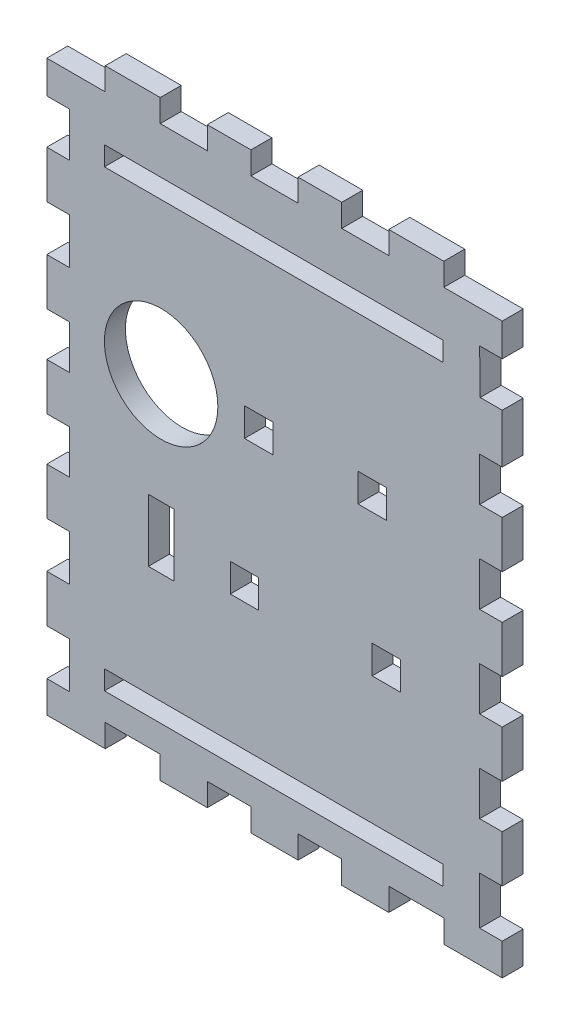
SolidWorks part; units mm, degrees
ref_plane "Front Plane" through (0, 0, 0) normal (0, 0, 1) x (1, 0, 0)
ref_plane "Top Plane" through (0, 0, 0) normal (0, 1, 0) x (1, 0, 0)
ref_plane "Right Plane" through (0, 0, 0) normal (1, 0, 0) x (0, 0, -1)
sketch "Model" plane through (0, 0, 0) normal (0, 0, 1) x (1, 0, 0)
  line L0 (11.6457, 131.1853) -> (7.6593, 131.1853)
  line L1 (7.6593, 131.1853) -> (7.6593, 139.4756)
  line L2 (7.6593, 139.4756) -> (11.6457, 139.4756)
  line L3 (11.6457, 139.4756) -> (11.6457, 147.1661)
  line L4 (11.6457, 147.1661) -> (7.6593, 147.1661)
  line L5 (7.6593, 147.1661) -> (7.6593, 155.4564)
  line L6 (7.6593, 155.4564) -> (11.6457, 155.4564)
  line L7 (11.6457, 155.4564) -> (11.6457, 163.1823)
  line L8 (11.6457, 163.1823) -> (7.6593, 163.1823)
  line L9 (7.6593, 163.1823) -> (7.6593, 171.4725)
  line L10 (7.6593, 171.4725) -> (11.6457, 171.4725)
  line L11 (87.9515, 101.1639) -> (77.6504, 101.1639)
  line L12 (77.6504, 101.1639) -> (77.6504, 105.1856)
  line L13 (77.6504, 105.1856) -> (67.949, 105.1856)
  line L14 (67.949, 105.1856) -> (67.949, 101.1639)
  line L15 (67.949, 101.1639) -> (59.6588, 101.1639)
  line L16 (59.6588, 101.1639) -> (59.6588, 105.1856)
  line L17 (59.6588, 105.1856) -> (51.9682, 105.1856)
  line L18 (51.9682, 105.1856) -> (51.9682, 101.1639)
  line L19 (51.9682, 101.1639) -> (43.6427, 101.1639)
  line L20 (43.6427, 101.1639) -> (43.6427, 105.1856)
  line L21 (43.6427, 105.1856) -> (35.9521, 105.1856)
  line L22 (35.9521, 105.1856) -> (35.9521, 101.1639)
  line L23 (35.9521, 101.1639) -> (27.6618, 101.1639)
  line L24 (27.6618, 101.1639) -> (27.6618, 105.1856)
  line L25 (27.6618, 105.1856) -> (17.9604, 105.1856)
  line L26 (17.9604, 105.1856) -> (17.9604, 101.1639)
  line L27 (17.9604, 101.1639) -> (7.6593, 101.1639)
  line L28 (87.9515, 179.1631) -> (83.9652, 179.1631)
  line L29 (83.9652, 179.1631) -> (83.9652, 171.4725)
  line L30 (83.9652, 171.4725) -> (87.9515, 171.4725)
  line L31 (87.9515, 171.4725) -> (87.9515, 163.1823)
  line L32 (87.9515, 163.1823) -> (83.9652, 163.1823)
  line L33 (83.9652, 163.1823) -> (83.9652, 155.4564)
  line L34 (83.9652, 155.4564) -> (87.9515, 155.4564)
  line L35 (87.9515, 155.4564) -> (87.9515, 147.1661)
  line L36 (87.9515, 147.1661) -> (83.9652, 147.1661)
  line L37 (83.9652, 147.1661) -> (83.9652, 139.4756)
  line L38 (83.9652, 139.4756) -> (87.9515, 139.4756)
  line L39 (87.9515, 139.4756) -> (87.9515, 131.1853)
  line L40 (87.9515, 131.1853) -> (83.9652, 131.1853)
  line L41 (87.9515, 201.4586) -> (77.6504, 201.4586)
  line L42 (77.6504, 201.4586) -> (77.6504, 205.445)
  line L43 (77.6504, 205.445) -> (67.949, 205.445)
  line L44 (67.949, 205.445) -> (67.949, 201.4586)
  line L45 (67.949, 201.4586) -> (59.6588, 201.4586)
  line L46 (59.6588, 201.4586) -> (59.6588, 205.445)
  line L47 (59.6588, 205.445) -> (51.9682, 205.445)
  line L48 (51.9682, 205.445) -> (51.9682, 201.4586)
  line L49 (51.9682, 201.4586) -> (43.6427, 201.4586)
  line L50 (43.6427, 201.4586) -> (43.6427, 205.445)
  line L51 (43.6427, 205.445) -> (35.9521, 205.445)
  line L52 (35.9521, 205.445) -> (35.9521, 201.4586)
  line L53 (35.9521, 201.4586) -> (27.6618, 201.4586)
  line L54 (27.6618, 201.4586) -> (27.6618, 205.445)
  line L55 (27.6618, 205.445) -> (17.9604, 205.445)
  line L56 (17.9604, 205.445) -> (17.9604, 201.4586)
  line L57 (17.9604, 201.4586) -> (7.6593, 201.4586)
  line L58 (17.8193, 193.3231) -> (77.5093, 193.3231)
  line L59 (77.5093, 193.3231) -> (77.5093, 189.9364)
  line L60 (77.5093, 189.9364) -> (17.8193, 189.9364)
  line L61 (17.8193, 189.9364) -> (17.8193, 193.3231)
  line L62 (17.8193, 113.3211) -> (77.5093, 113.3211)
  line L63 (77.5093, 113.3211) -> (77.5093, 109.9345)
  line L64 (77.5093, 109.9345) -> (17.8193, 109.9345)
  line L65 (17.8193, 109.9345) -> (17.8193, 113.3211)
  line L66 (11.6457, 179.5377) -> (7.6593, 179.5377)
  line L67 (7.6593, 179.5377) -> (7.6593, 187.8633)
  line L68 (7.6593, 187.8633) -> (11.6457, 187.8633)
  line L69 (11.6457, 187.8633) -> (11.6457, 195.686)
  line L70 (11.6457, 171.4725) -> (11.6457, 179.5377)
  line L71 (11.6457, 195.686) -> (7.6593, 195.686)
  line L72 (7.6593, 195.686) -> (7.6593, 201.4586)
  line L73 (11.6457, 114.7946) -> (7.6593, 114.7946)
  line L74 (7.6593, 114.7946) -> (7.6593, 123.1201)
  line L75 (7.6593, 123.1201) -> (11.6457, 123.1201)
  line L76 (11.6457, 123.1201) -> (11.6457, 131.1853)
  line L77 (7.6593, 101.1639) -> (7.6593, 106.7294)
  line L78 (7.6593, 106.7294) -> (11.6457, 106.7294)
  line L79 (11.6457, 106.7294) -> (11.6457, 114.7946)
  line L80 (83.9652, 131.1853) -> (83.9652, 123.4948)
  line L81 (83.9652, 123.4948) -> (87.9515, 123.4948)
  line L82 (87.9515, 123.4948) -> (87.9515, 115.2045)
  line L83 (87.9515, 115.2045) -> (83.9652, 115.2045)
  line L84 (83.9652, 115.2045) -> (83.9652, 106.7865)
  line L85 (83.9652, 106.7865) -> (87.9515, 106.7865)
  line L86 (87.9515, 106.7865) -> (87.9515, 101.1639)
  line L87 (83.9652, 195.686) -> (84.0662, 187.8513)
  line L88 (87.9515, 195.686) -> (83.9652, 195.686)
  line L89 (87.9515, 201.4586) -> (87.9515, 195.686)
  line L90 (87.9515, 187.8513) -> (87.9515, 179.1631)
  line L91 (84.0662, 187.8513) -> (88.0526, 187.8513)
extrude "Boss-Extrude1" add sketch "Model" along normal blind 3.7 contours L91 L87 L88 L89 L41 L42 L43 L44 L45 L46 L47 L48 L49 L50 L51 L52 L53 L54 L55 L56 L57 L72 L71 L69 L68 L67 L66 L70 L10 L9 L8 L7 L6 L5 L4 L3 L2 L1 L0 L76 L75 L74 L73 L79 L78 L77 L27 L26 L25 L24 L23
sketch "Sketch1" plane through (0, 0, 3.7) normal (0, 0, 1) x (1, 0, 0)
  line L0 (40.0093, 140.8211) -> (40.0093, 135.8211)
  line L1 (17.8193, 113.3211) -> (27.8193, 113.3211)
  line L2 (17.8193, 113.3211) -> (17.8193, 138.3211)
  line L3 (17.8193, 138.3211) -> (27.8193, 138.3211)
  line L4 (27.8193, 113.3211) -> (27.8193, 138.3211)
  line L5 (25.5693, 143.8211) -> (30.0693, 143.8211)
  line L6 (25.5693, 143.8211) -> (25.5693, 132.8211)
  line L7 (25.5693, 132.8211) -> (30.0693, 132.8211)
  line L8 (30.0693, 143.8211) -> (30.0693, 132.8211)
  line L9 (25.5693, 143.8211) -> (30.0693, 132.8211) construction
  line L10 (25.5693, 132.8211) -> (30.0693, 143.8211) construction
  line L11 (77.5093, 113.3211) -> (67.5093, 113.3211)
  line L12 (77.5093, 113.3211) -> (77.5093, 138.3211)
  line L13 (77.5093, 138.3211) -> (67.5093, 138.3211)
  line L14 (67.5093, 113.3211) -> (67.5093, 138.3211)
  line L15 (65.0093, 140.8211) -> (70.0093, 140.8211)
  line L16 (65.0093, 140.8211) -> (65.0093, 135.8211)
  line L17 (65.0093, 135.8211) -> (70.0093, 135.8211)
  line L18 (70.0093, 140.8211) -> (70.0093, 135.8211)
  line L19 (65.0093, 140.8211) -> (70.0093, 135.8211) construction
  line L20 (65.0093, 135.8211) -> (70.0093, 140.8211) construction
  line L21 (40.0093, 140.8211) -> (45.0093, 140.8211)
  line L22 (45.0093, 140.8211) -> (45.0093, 135.8211)
  line L23 (40.0093, 135.8211) -> (45.0093, 135.8211)
  line L24 (65.0093, 138.3211) -> (45.0093, 138.3211)
  line L25 (55.0093, 138.3211) -> (55.0093, 163.3211)
  line L26 (45.0093, 163.3211) -> (65.0093, 163.3211)
  line L27 (42.5093, 165.8211) -> (42.5093, 160.8211)
  line L28 (62.5093, 165.8211) -> (67.5093, 165.8211)
  line L29 (62.5093, 165.8211) -> (62.5093, 160.8211)
  line L30 (62.5093, 160.8211) -> (67.5093, 160.8211)
  line L31 (67.5093, 165.8211) -> (67.5093, 160.8211)
  line L32 (62.5093, 165.8211) -> (67.5093, 160.8211) construction
  line L33 (62.5093, 160.8211) -> (67.5093, 165.8211) construction
  line L34 (42.5093, 160.8211) -> (47.5093, 160.8211)
  line L35 (42.5093, 165.8211) -> (47.5093, 165.8211)
  line L36 (47.5093, 165.8211) -> (47.5093, 160.8211)
  line L37 (62.5093, 165.8211) -> (42.5093, 165.8211) construction
  line L38 (27.8193, 143.8211) -> (27.8193, 163.3211)
  circle A0 centre (27.8193, 163.3211) radius 10
  point P29 (55.0093, 163.3211)
  dimension "D1" = 25
  dimension "D2" = 10
  dimension "D3" = 11
  dimension "D4" = 4.5
  dimension "D5" = 10
  dimension "D6" = 25
  dimension "D7" = 5
  dimension "D8" = 5
  dimension "D10" = 25
  dimension "D11" = 5
  dimension "D12" = 5
  dimension "D14" = 20
  dimension "D15" = 19.5
  dimension "D9" = 2
  dimension "D13" = 2
extrude "Cut-Extrude1" cut sketch "Sketch1" against normal blind 10
